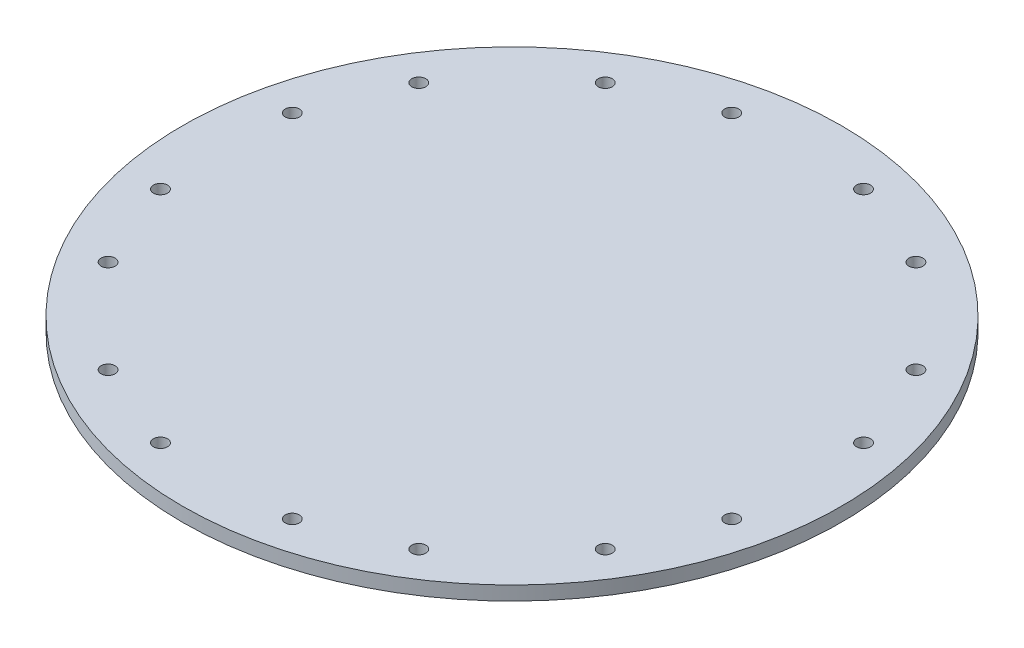
SolidWorks part; units mm, degrees
material "Acrylic (Medium-high impact)"
ref_plane "Front Plane" through (0, 0, 0) normal (0, 0, 1) x (1, 0, 0)
ref_plane "Top Plane" through (0, 0, 0) normal (0, 1, 0) x (1, 0, 0)
ref_plane "Right Plane" through (0, 0, 0) normal (1, 0, 0) x (0, 0, -1)
sketch "Sketch1" plane through (0, 0, 0) normal (0, 1, 0) x (1, 0, 0)
  line L1 (-70, 230) -> (70, 230) construction
  line L14 (-70, 230) -> (-30, 130) construction
  line L15 (-30, 130) -> (30, 130) construction
  line L16 (70, 230) -> (30, 130) construction
  circle A7 centre (0, 0) radius 250
  circle A10 centre (0, 0) radius 230 construction
  circle A11 centre (0, 230) radius 3 construction
  circle A12 centre (162.6346, 162.6346) radius 3 construction
  circle A13 centre (230, 0) radius 3 construction
  circle A53 centre (-70, 230) radius 3 construction
  circle A54 centre (70, 230) radius 3 construction
  circle A55 centre (30, 130) radius 3 construction
  circle A56 centre (-30, 130) radius 3 construction
  circle A57 centre (212.132, 113.1371) radius 3 construction
  circle A58 centre (113.1371, 70.7107) radius 3 construction
  circle A59 centre (162.6346, -162.6346) radius 3 construction
  circle A60 centre (0, -230) radius 3 construction
  circle A61 centre (-162.6346, -162.6346) radius 3 construction
  circle A62 centre (-230, 0) radius 3 construction
  circle A63 centre (-162.6346, 162.6346) radius 3 construction
  circle A65 centre (70.7107, 113.1371) radius 3 construction
  circle A66 centre (113.1371, 212.132) radius 3 construction
  circle A67 centre (230, -70) radius 3 construction
  circle A68 centre (130, -30) radius 3 construction
  circle A69 centre (130, 30) radius 3 construction
  circle A70 centre (230, 70) radius 3 construction
  circle A71 centre (113.1371, -212.132) radius 3 construction
  circle A72 centre (70.7107, -113.1371) radius 3 construction
  circle A73 centre (113.1371, -70.7107) radius 3 construction
  circle A74 centre (212.132, -113.1371) radius 3 construction
  circle A75 centre (-70, -230) radius 3 construction
  circle A76 centre (-30, -130) radius 3 construction
  circle A77 centre (30, -130) radius 3 construction
  circle A78 centre (70, -230) radius 3 construction
  circle A79 centre (-212.132, -113.1371) radius 3 construction
  circle A80 centre (-113.1371, -70.7107) radius 3 construction
  circle A81 centre (-70.7107, -113.1371) radius 3 construction
  circle A82 centre (-113.1371, -212.132) radius 3 construction
  circle A83 centre (-230, 70) radius 3 construction
  circle A84 centre (-130, 30) radius 3 construction
  circle A85 centre (-130, -30) radius 3 construction
  circle A86 centre (-230, -70) radius 3 construction
  circle A87 centre (-113.1371, 212.132) radius 3 construction
  circle A88 centre (-70.7107, 113.1371) radius 3 construction
  circle A89 centre (-113.1371, 70.7107) radius 3 construction
  circle A90 centre (-212.132, 113.1371) radius 3 construction
  circle A91 centre (0, 70) radius 3 construction
  circle A92 centre (0, 0) radius 150
  point P28 (0, 0)
  point P32 (0, 230)
  point P38 (0, 130)
  point P95 (0, 0)
  point P113 (0, 0)
  point P217 (0, 0)
  dimension "D1" = 460
  dimension "D2" = 8
  dimension "D4" = 500
  dimension "D5" = 300
  dimension "D7" = 60
  dimension "D8" = 6
  dimension "D10" = 140
  dimension "D12" = 60
  dimension "D3" = 6
  dimension "D9" = 130
  dimension "D6" = 100
  dimension "D11" = 8
extrude "Boss-Extrude1" add sketch "Sketch1" against normal blind 6.35 contours A92 | A7
hole_wizard "M6 Clearance Hole1" positions "3DSketch2" profile "Sketch3" hole size "M6" standard "ANSI Metric" end condition through all
sketch3d "3DSketch2"
  point P18 (-30, 0, -130)
  point P20 (30, 0, -130)
  point P23 (-30, 0, -130)
  point P25 (30, 0, -130)
sketch "Sketch3" plane through (-30, 0, -130) normal (1, 0, 0) x (0, 0, 1)
  line L0 (0, 0) -> (0, 6.35)
  line L1 (0, 6.35) -> (3.2, 6.35)
  line L2 (3.2, 6.35) -> (3.2, 0)
  line L5 (3.2, 0) -> (0, 0)
  line L11 (0, -6.35) -> (0, 107.95) construction
  dimension "Thru Hole Dia." = 6.4
  dimension "Thru Hole Depth" = 6.35
pattern_circular "CirPattern1" count 8 over 360 about axis through (0, 0, 0) along (0, 1, 0) of "M6 Clearance Hole1"
